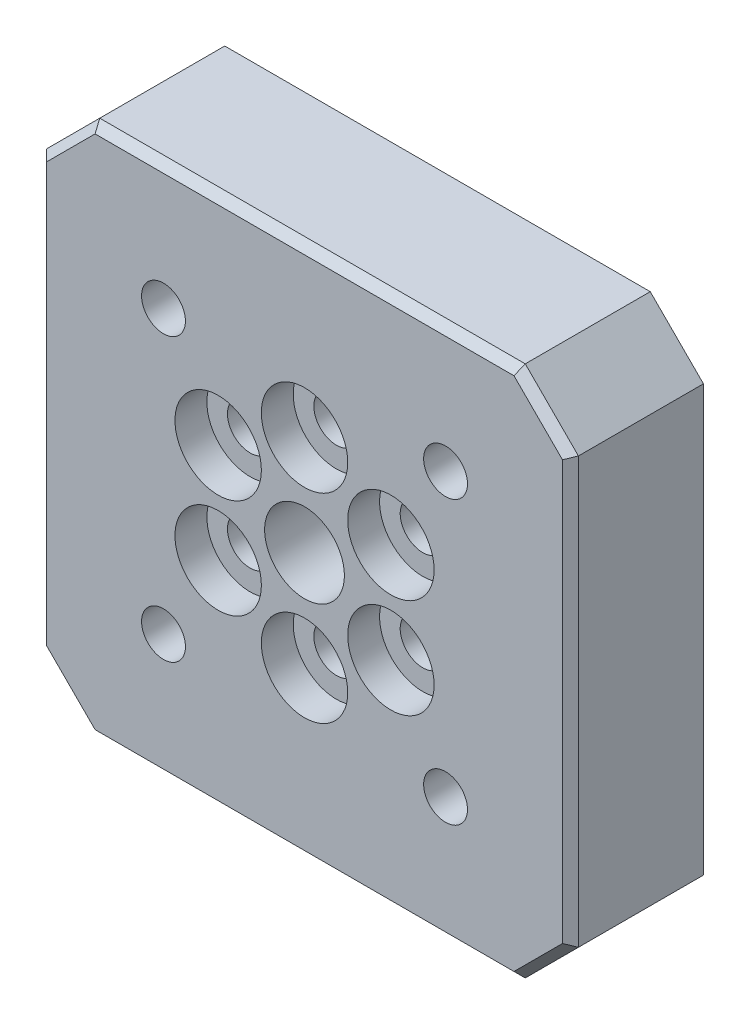
SolidWorks part; units mm, degrees
material "6061-T6 (SS)"
ref_plane "Front Plane" through (0, 0, 0) normal (0, 0, 1) x (1, 0, 0)
ref_plane "Top Plane" through (0, 0, 0) normal (0, 1, 0) x (1, 0, 0)
ref_plane "Right Plane" through (0, 0, 0) normal (1, 0, 0) x (0, 0, -1)
sketch "Sketch1" plane through (0, 0, 0) normal (0, 0, 1) x (1, 0, 0)
  line L1 (0, 0) -> (40, 0)
  line L2 (0, 0) -> (0, 40)
  line L3 (0, 40) -> (40, 40)
  line L4 (40, 0) -> (40, 40)
  dimension "D2" = 40
extrude "Boss-Extrude1" add sketch "Sketch1" along normal blind 10
sketch "Sketch2" plane through (0, 0, 10) normal (0, 0, 1) x (1, 0, 0)
  line L0 (0, 40) -> (40, 0) construction
  line L1 (40, 0) -> (40, 40) construction
  line L2 (40, 40) -> (0, 0) construction
  line L3 (40, 40) -> (0, 40) construction
  point P12 (20, 20)
hole_wizard "Ø6.0mm Dowel Hole1" positions "Sketch2" profile "Sketch3" hole size "Ø6.0" standard "DIN" end condition through all
sketch "Sketch3" plane through (20, 20, 10) normal (1, 0, 0) x (0, -1, 0)
  line L0 (0, 0) -> (0, 10)
  line L1 (0, 10) -> (3, 10)
  line L2 (3, 10) -> (3, 0)
  line L5 (3, 0) -> (0, 0)
  line L11 (0, -6.35) -> (0, 107.95) construction
  dimension "Thru Hole Dia." = 6
  dimension "Thru Hole Depth" = 10
sketch "Sketch10" plane through (0, 0, 10) normal (0, 0, 1) x (1, 0, 0)
  circle A0 centre (20, 20) radius 7.5
  point P5 (20, 27.5)
  point P12 (26.4952, 23.75)
  point P13 (26.4952, 16.25)
  point P14 (20, 12.5)
  point P15 (13.5048, 16.25)
  point P16 (13.5048, 23.75)
  dimension "D1" = 15
  dimension "D2" = 6
hole_wizard "CBORE for M3 Hex Socket Thin Head Cap Screw4" positions "Sketch10" profile "Sketch11" counterbore size "M3" standard "DIN" end condition through all
sketch "Sketch11" plane through (13.5048, 23.75, 10) normal (1, 0, 0) x (0, -1, 0)
  line L0 (0, 0) -> (0, 10)
  line L1 (0, 10) -> (1.7, 10)
  line L3 (1.7, 10) -> (1.7, 2.4)
  line L4 (1.7, 2.4) -> (3.25, 2.4)
  line L5 (3.25, 2.4) -> (3.25, 0)
  line L7 (3.25, 0) -> (0, 0)
  line L11 (0, -6.35) -> (0, 107.95) construction
  dimension "Thru Hole Dia." = 3.4
  dimension "Thru Hole Depth" = 10
  dimension "C'Bore Dia." = 6.5
  dimension "C'Bore Depth" = 2.4
sketch "Sketch12" plane through (0, 0, 10) normal (0, 0, 1) x (1, 0, 0)
  line L0 (20, 20) -> (9.3934, 30.6066) construction
  circle A0 centre (20, 20) radius 15
  point P4 (9.3934, 30.6066)
  point P11 (30.6066, 30.6066)
  point P12 (30.6066, 9.3934)
  point P13 (9.3934, 9.3934)
  dimension "D1" = 30
  dimension "D3" = 45
  dimension "D2" = 4
hole_wizard "Tap Drill for M4 Tap1" positions "Sketch12" profile "Sketch13" hole size "M4" standard "DIN" end condition through all
sketch "Sketch13" plane through (9.3934, 9.3934, 10) normal (1, 0, 0) x (0, -1, 0)
  line L0 (0, 0) -> (0, 10)
  line L1 (0, 10) -> (1.65, 10)
  line L2 (1.65, 10) -> (1.65, 0)
  line L5 (1.65, 0) -> (0, 0)
  line L11 (0, -6.35) -> (0, 107.95) construction
  dimension "Thru Hole Dia." = 3.3
  dimension "Thru Hole Depth" = 10
chamfer "Chamfer1" distance 4 angle 45 4 edges at (40, 0, 5) (40, 40, 5) (0, 0, 5) (0, 40, 5)
chamfer "Chamfer2" distance 0.6 angle 45 8 edges at (40, 20, 10) (38, 38, 10) (38, 2, 10) (20, 0, 10) (2, 2, 10) (0, 20, 10) (2, 38, 10) (20, 40, 10)
